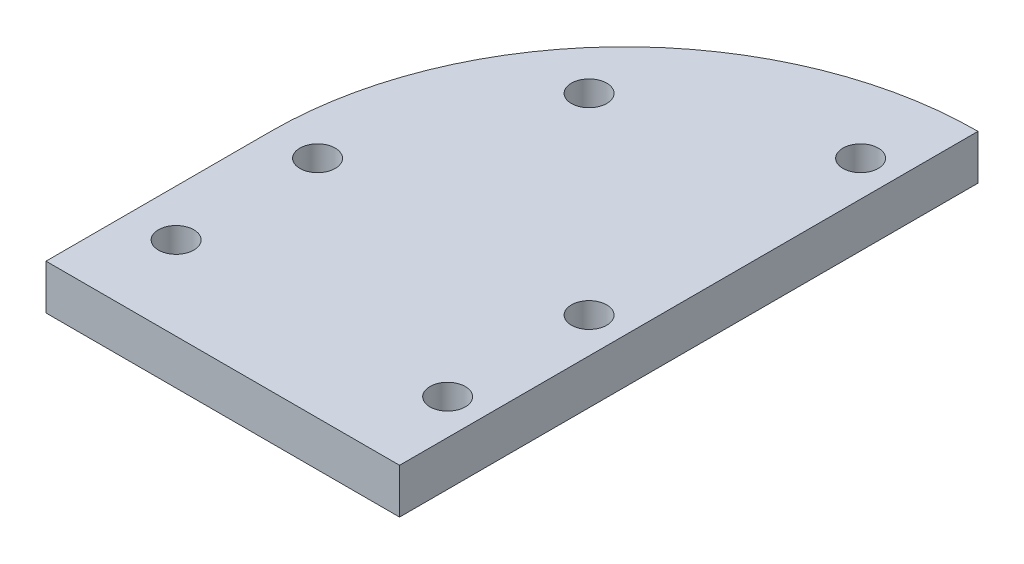
SolidWorks part; units mm, degrees
ref_plane "Front Plane" through (0, 0, 0) normal (0, 0, 1) x (1, 0, 0)
ref_plane "Top Plane" through (0, 0, 0) normal (0, 1, 0) x (1, 0, 0)
ref_plane "Right Plane" through (0, 0, 0) normal (1, 0, 0) x (0, 0, -1)
sketch "Sketch2" plane through (0, 0, 0) normal (0, 1, 0) x (1, 0, 0)
  line L0 (50, 31.8) -> (50, 81.8)
  line L1 (0, 0) -> (50, 0)
  line L2 (0, 0) -> (0, 31.8)
  line L4 (50, 0) -> (50, 31.8)
  line L6 (45, 31.8) -> (17.8471, 58.9529) construction
  line L8 (45, 31.8) -> (6.6, 31.8) construction
  line L9 (45, 31.8) -> (45, 70.2) construction
  circle A0 centre (45, 31.8) radius 2.5
  circle A1 centre (6.6, 31.8) radius 2.5
  arc A2 (0, 31.8) -> (50, 81.8) centre (50, 31.8) cw
  circle A4 centre (17.8471, 58.9529) radius 2.5
  circle A7 centre (45, 70.2) radius 2.5
  circle A9 centre (6.6, 11.8) radius 2.5
  circle A10 centre (45, 11.8) radius 2.5
  dimension "D3" = 5
  dimension "D14" = 11.8
  dimension "D2" = 50
  dimension "D4" = 20
  dimension "D5" = 5
  dimension "D6" = 38.4
  dimension "D9" = 45
extrude "Boss-Extrude1" add sketch "Sketch2" along normal blind 6.35
